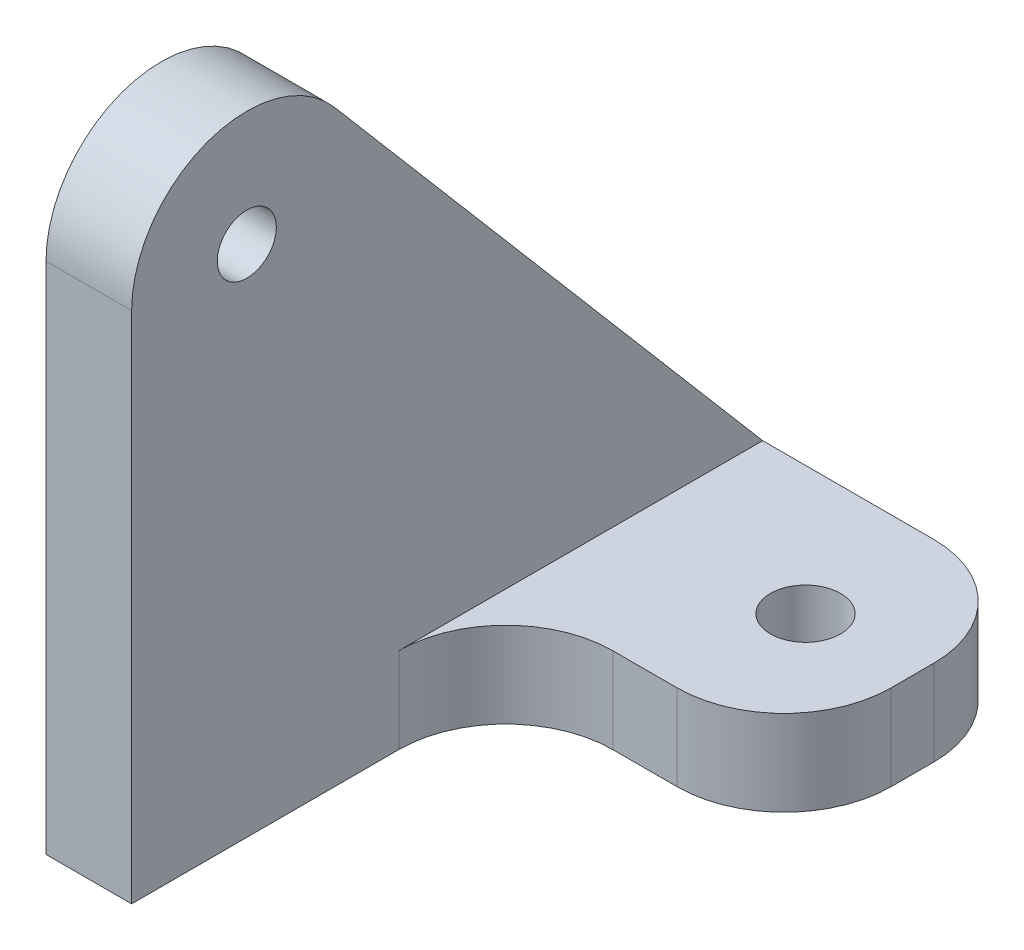
SolidWorks part; units mm, degrees
ref_plane "Front Plane" through (0, 0, 0) normal (0, 0, 1) x (1, 0, 0)
ref_plane "Top Plane" through (0, 0, 0) normal (0, 1, 0) x (1, 0, 0)
ref_plane "Right Plane" through (0, 0, 0) normal (1, 0, 0) x (0, 0, -1)
sketch "Sketch1" plane through (0, 0, 0) normal (0, 1, 0) x (1, 0, 0)
  line L1 (-12.7, -7.62) -> (12.7, -7.62)
  line L2 (-19.05, -1.27) -> (-19.05, 1.27)
  line L3 (-12.7, 7.62) -> (12.7, 7.62)
  line L4 (19.05, -1.27) -> (19.05, 1.27)
  line L5 (-19.05, -7.62) -> (19.05, 7.62) construction
  line L6 (-19.05, 7.62) -> (19.05, -7.62) construction
  arc A0 (19.05, 1.27) -> (12.7, 7.62) centre (12.7, 1.27) ccw
  arc A1 (-19.05, 1.27) -> (-12.7, 7.62) centre (-12.7, 1.27) cw
  arc A2 (19.05, -1.27) -> (12.7, -7.62) centre (12.7, -1.27) cw
  arc A3 (-12.7, -7.62) -> (-19.05, -1.27) centre (-12.7, -1.27) cw
  circle A4 centre (-12.7, 0) radius 2.0828
  circle A5 centre (12.7, 0) radius 2.0828
  point P0 (0, 0)
  dimension "D1" = 6.35
  dimension "D4" = 6.35
  dimension "D5" = 12.7
  dimension "D7" = 4.1656
  dimension "D2" = 38.1
  dimension "D3" = 15.24
  dimension "D6" = 12.7
extrude "Boss-Extrude1" add sketch "Sketch1" along normal blind 5.08
sketch "Sketch2" plane through (0, 0, 0) normal (1, 0, 0) x (0, 0, -1)
  line L0 (7.62, 5.08) -> (-17.7852, 34.9101)
  line L1 (7.62, 5.08) -> (1.27, 5.08) construction
  line L2 (-29.8196, 30.48) -> (-29.8196, 0)
  line L3 (-29.8196, 0) -> (7.62, 0)
  line L4 (-1.27, 5.08) -> (1.27, 5.08) construction
  line L5 (7.62, 0) -> (7.62, 5.08)
  line L6 (7.62, 5.08) -> (7.62, 0) construction
  arc A0 (-29.8196, 30.48) -> (-17.7852, 34.9101) centre (-22.987, 30.48) cw
  circle A1 centre (-22.987, 30.48) radius 1.7526
  point P6 (-29.8196, 11.1597)
  point P15 (-14.7993, 0)
  point P17 (-17.1196, 0.4465)
  dimension "D1" = 3.5052
  dimension "D5" = 5.08
  dimension "D2" = 22.987
  dimension "D3" = 25.4
extrude "Boss-Extrude2" add sketch "Sketch2" along normal mid plane 5.08
fillet "Fillet1" radius 6.35 2 edges at (-2.54, 2.54, 7.62) (2.54, 2.54, 7.62)
